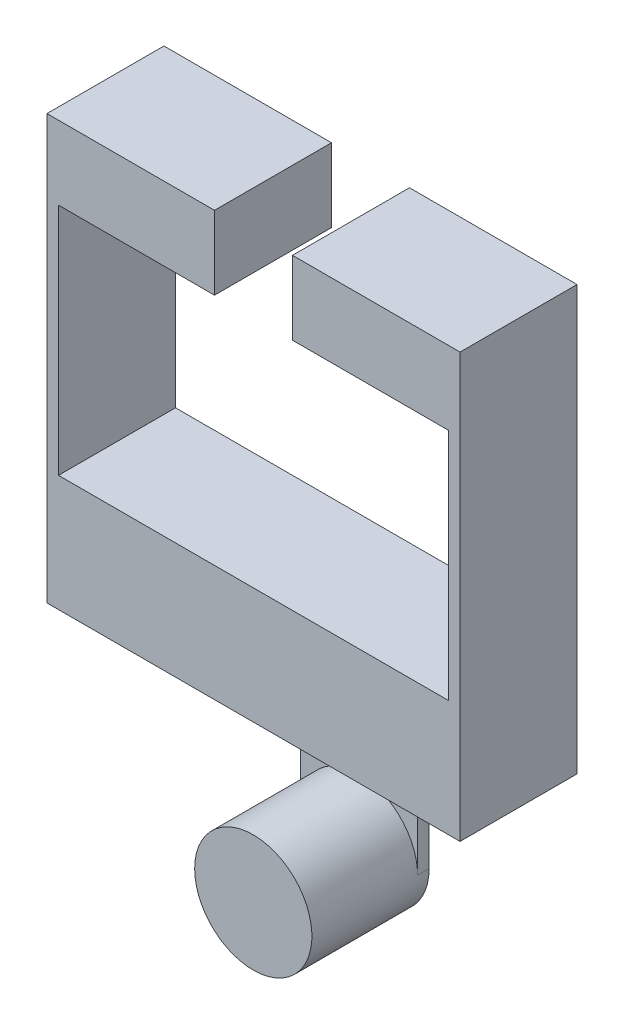
SolidWorks part; units mm, degrees
ref_plane "Front Plane" through (0, 0, 0) normal (0, 0, 1) x (1, 0, 0)
ref_plane "Top Plane" through (0, 0, 0) normal (0, 1, 0) x (1, 0, 0)
ref_plane "Right Plane" through (0, 0, 0) normal (1, 0, 0) x (0, 0, -1)
sketch "Sketch1" plane through (0, 0, 0) normal (0, 0, 1) x (1, 0, 0)
  line L0 (0, 28.5155) -> (0, -34.5029) construction
  line L2 (-33.6315, 34.5029) -> (-33.6315, -34.5029)
  line L3 (-33.6315, -34.5029) -> (33.6315, -34.5029)
  line L4 (33.6315, 34.5029) -> (33.6315, -34.5029)
  line L5 (-33.6315, 34.5029) -> (33.6315, -34.5029) construction
  line L6 (-33.6315, -34.5029) -> (33.6315, 34.5029) construction
  line L7 (-33.6315, 0) -> (33.6315, 0) construction
  line L8 (6.35, 34.5029) -> (6.35, 22.5292)
  line L9 (-6.35, 34.5029) -> (-6.35, 22.5292)
  line L10 (6.35, 22.5292) -> (31.75, 22.5292)
  line L11 (-6.35, 22.5292) -> (-31.75, 22.5292)
  line L12 (31.75, 22.5292) -> (31.75, -15.5708)
  line L13 (-31.75, 22.5292) -> (-31.75, -15.5708)
  line L14 (31.75, -15.5708) -> (-31.75, -15.5708)
  line L15 (-33.6315, 34.5029) -> (-6.35, 34.5029)
  line L16 (33.6315, 34.5029) -> (6.35, 34.5029)
  point P0 (0, 0)
  point P18 (0, -15.5708)
  dimension "D1" = 63.5
  dimension "D2" = 38.1
  dimension "D3" = 11.9737
  dimension "D4" = 25.4
  dimension "D5" = 18.932
  dimension "D6" = 1.8815
extrude "Boss-Extrude1" add sketch "Sketch1" along normal blind 19.05
sketch "Sketch2" plane through (0, -34.5029, 0) normal (0, -1, 0) x (1, 0, 0)
  line L0 (0, 19.05) -> (0, 0) construction
  line L1 (-9.5441, 0) -> (-9.5441, 1.8777)
  line L2 (9.5441, 0) -> (9.5441, 1.8777)
  line L3 (-9.5441, 1.8777) -> (9.5441, 1.8777)
  line L4 (-33.6315, 0) -> (33.6315, 0)
  line L5 (33.6315, 0) -> (33.6315, 19.05)
  line L6 (33.6315, 19.05) -> (-33.6315, 19.05)
  line L7 (-33.6315, 19.05) -> (-33.6315, 0)
  line L8 (-33.6315, 0) -> (33.6315, 0)
  line L9 (33.6315, 0) -> (33.6315, 19.05)
  line L10 (33.6315, 19.05) -> (-33.6315, 19.05)
  line L11 (-33.6315, 19.05) -> (-33.6315, 0)
  point P11 (0, 1.8777)
  dimension "D2" = 1.8777
  dimension "D3" = 19.0881
  dimension "D1" = 0
extrude "Boss-Extrude3" add sketch "Sketch2" along normal blind 25.4 contours L0 L3 L1 | L3 L0 L8 L2
sketch "Sketch3" plane through (0, 0, 0) normal (0, 0, -1) x (-1, 0, 0)
  line L0 (0, 34.1058) -> (0, -64.9309) construction
  line L1 (9.5441, -59.9029) -> (-9.5441, -59.9029) construction
  line L2 (9.5441, -59.9029) -> (-9.5441, -59.9029)
  circle A0 centre (0, -59.9029) radius 9.5441
  dimension "D1" = 19.0881
extrude "Boss-Extrude4" add sketch "Sketch3" against normal blind 19.0881
equation "\"force\"= 500"
equation "\"W\"= 2 * \"force\""
equation "\"length1\"= 0.75"
equation "\"stressAllowable\"= 9000"
equation "\"z1\"= ( \"W\" * \"length1\" ) / ( \"stressAllowable\" * 2 )"
equation "\"d1\"= ( ( \"z1\" * 32 ) / ( pi ) ) ^ ( 1 / 3 )"
equation "\"t2\"= ( \"W\" ) / ( \"stressAllowable\" * \"d1\" * 2 )"
equation "\"l3\"= 2.5"
equation "\"b3\"= 0.75"
equation "\"d3\"= ( ( \"W\" * \"l3\" * 3 ) / ( \"b3\" * \"stressAllowable\" * 2 ) ) ^ ( 1 / 2 )"
equation "\"t4\"= ( \"W\" * 2 ) / ( \"stressAllowable\" * 3 )"
equation "\"b5\"= \"b3\""
equation "\"l5\"= 1"
equation "\"z5\"= ( \"W\" * \"l5\" * 0.5 ) / ( \"stressAllowable\" * 2 )"
equation "\"h5\"= ( ( \"z5\" * 6 ) / ( \"b5\" ) ) ^ ( 1 / 2 )"
equation "\"D1@Sketch1\"=\"l3\""
equation "\"l4\"= 1.5"
equation "\"D2@Sketch1\"=\"l4\""
equation "\"D3@Sketch1\"=\"h5\""
equation "\"D4@Sketch1\"=\"l5\""
equation "\"D5@Sketch1\"=\"d3\""
equation "\"D6@Sketch1\"=\"t4\""
equation "\"D1@Boss-Extrude1\"=\"b3\""
equation "\"D2@Sketch2\"=\"t2\""
equation "\"D1@Boss-Extrude4\"=\"d1\""
equation "\"D3@Sketch2\"=\"d1\""
